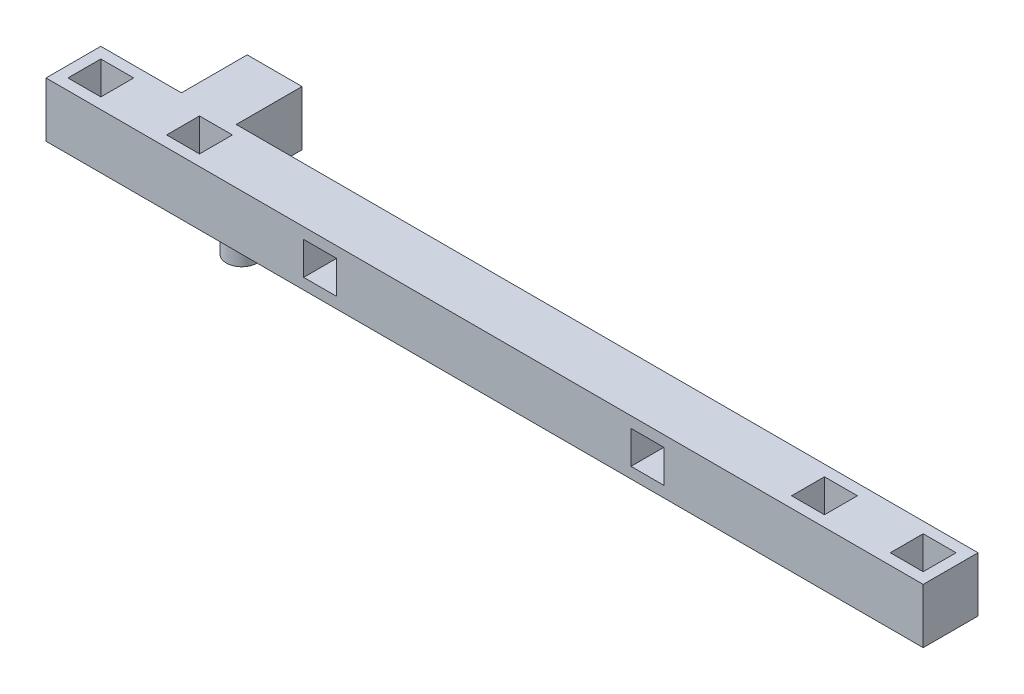
SolidWorks part; units mm, degrees
ref_plane "Front Plane" through (0, 0, 0) normal (0, 0, 1) x (1, 0, 0)
ref_plane "Top Plane" through (0, 0, 0) normal (0, 1, 0) x (1, 0, 0)
ref_plane "Right Plane" through (0, 0, 0) normal (1, 0, 0) x (0, 0, -1)
sketch "Sketch1" plane through (0, 0, 0) normal (0, 0, 1) x (1, 0, 0)
  line L1 (0, 0) -> (80, 0)
  line L2 (0, 0) -> (0, 5)
  line L3 (0, 5) -> (80, 5)
  line L4 (80, 0) -> (80, 5)
  line L5 (53.35, 4) -> (56.35, 4)
  line L6 (53.35, 4) -> (53.35, 1)
  line L7 (53.35, 1) -> (56.35, 1)
  line L8 (56.35, 4) -> (56.35, 1)
  line L9 (23.5, 4) -> (26.5, 4)
  line L10 (23.5, 4) -> (23.5, 1)
  line L11 (23.5, 1) -> (26.5, 1)
  line L12 (26.5, 4) -> (26.5, 1)
  dimension "D1" = 80
  dimension "D2" = 5
  dimension "D3" = 3
  dimension "D4" = 3
  dimension "D5" = 3
  dimension "D6" = 3
  dimension "D7" = 1
  dimension "D8" = 1
  dimension "D9" = 23.65
  dimension "D10" = 53.5
extrude "Boss-Extrude1" add sketch "Sketch1" along normal blind 5
sketch "Sketch2" plane through (0, 5, 0) normal (0, 1, 0) x (1, 0, 0)
  line L0 (80, 0) -> (0, 0) construction
  line L1 (76, -1) -> (79, -1)
  line L2 (76, -1) -> (76, -4)
  line L3 (76, -4) -> (79, -4)
  line L4 (79, -1) -> (79, -4)
  line L5 (1, -1) -> (4, -1)
  line L6 (1, -1) -> (1, -4)
  line L7 (1, -4) -> (4, -4)
  line L8 (4, -1) -> (4, -4)
  line L9 (80, -5) -> (80, 0) construction
  line L10 (0, -5) -> (0, 0) construction
  line L11 (80, -5) -> (0, -5) construction
  line L12 (10, -1) -> (13, -1)
  line L13 (10, -1) -> (10, -4)
  line L14 (10, -4) -> (13, -4)
  line L15 (13, -1) -> (13, -4)
  line L16 (67, -1) -> (70, -1)
  line L17 (67, -1) -> (67, -4)
  line L18 (67, -4) -> (70, -4)
  line L19 (70, -1) -> (70, -4)
  point P14 (0, -2.5)
  dimension "D1" = 3
  dimension "D2" = 3
  dimension "D3" = 1
  dimension "D4" = 1
  dimension "D5" = 1
  dimension "D6" = 1
  dimension "D7" = 3
  dimension "D8" = 3
  dimension "D9" = 3
  dimension "D10" = 3
  dimension "D11" = 1
  dimension "D12" = 6
  dimension "D13" = 3
  dimension "D14" = 3
  dimension "D15" = 1
  dimension "D16" = 6
extrude "Cut-Extrude1" cut sketch "Sketch2" against normal blind 5
sketch "Sketch3" plane through (0, 0, 0) normal (0, 0, -1) x (-1, 0, 0)
  line L0 (-53.35, 4) -> (-53.35, 1) construction
  line L1 (-12.35, 5) -> (-7.35, 5)
  line L2 (-12.35, 5) -> (-12.35, 0)
  line L3 (-12.35, 0) -> (-7.35, 0)
  line L4 (-7.35, 5) -> (-7.35, 0)
  line L5 (-80, 5) -> (0, 5) construction
  dimension "D1" = 41
  dimension "D2" = 5
  dimension "D3" = 5
  dimension "D4" = 0
extrude "Boss-Extrude2" add sketch "Sketch3" along normal blind 6
sketch "Sketch4" plane through (0, 0, 0) normal (0, -1, 0) x (1, 0, 0)
  line L0 (0, 0) -> (7.35, 0) construction
  line L1 (12.35, -6) -> (12.35, 0) construction
  circle A0 centre (9.85, -3) radius 1.4
  dimension "D1" = 2.8
  dimension "D2" = 3
  dimension "D3" = 2.5
extrude "Boss-Extrude3" add sketch "Sketch4" along normal blind 8
